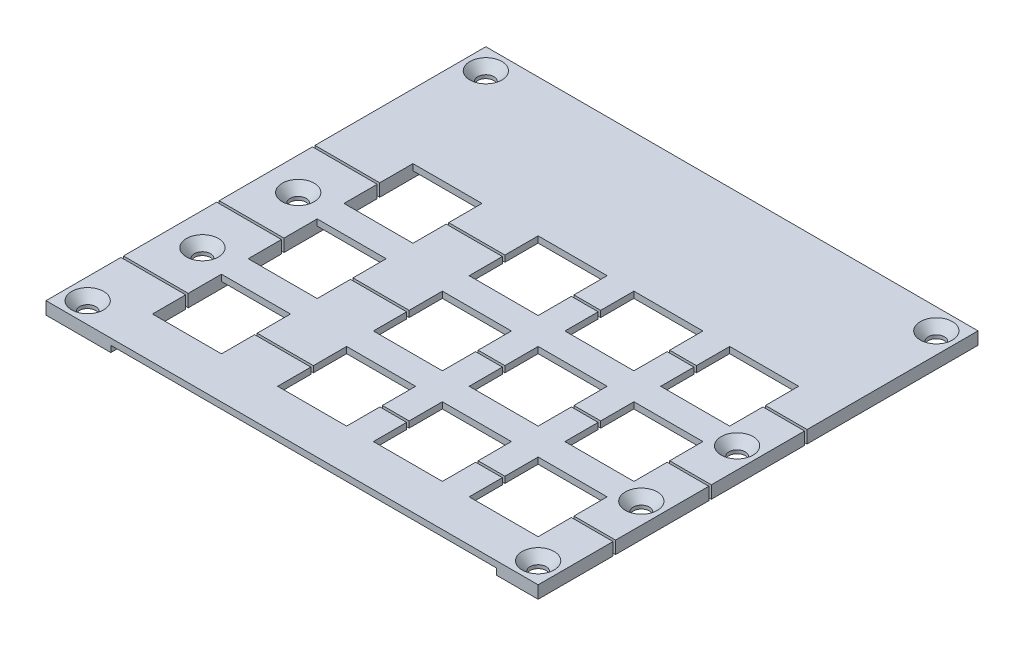
SolidWorks part; units mm, degrees
ref_plane "Front" through (0, 0, 0) normal (0, 0, 1) x (1, 0, 0)
ref_plane "Top" through (0, 0, 0) normal (0, 1, 0) x (1, 0, 0)
ref_plane "Right" through (0, 0, 0) normal (1, 0, 0) x (0, 0, -1)
sketch "Sketch1" plane through (0, 0, 0) normal (0, 1, 0) x (1, 0, 0)
  line L0 (2.6035, 2.6797) -> (8.0137, 2.6797) construction
  line L1 (-49.7332, -44.45) -> (49.7332, -44.45)
  line L2 (-49.7332, -44.45) -> (-49.7332, 44.45)
  line L3 (-49.7332, 44.45) -> (49.7332, 44.45)
  line L4 (49.7332, -44.45) -> (49.7332, 44.45)
  line L5 (-49.7332, -44.45) -> (49.7332, 44.45) construction
  line L6 (-49.7332, 44.45) -> (49.7332, -44.45) construction
  line L7 (-11.3411, 16.6243) -> (2.6035, 16.6243)
  line L8 (-11.3411, 16.6243) -> (-11.3411, 2.6797)
  line L9 (-11.3411, 2.6797) -> (2.6035, 2.6797)
  line L10 (2.6035, 16.6243) -> (2.6035, 2.6797)
  line L11 (8.0137, 16.6243) -> (21.9583, 16.6243)
  line L12 (8.0137, 16.6243) -> (8.0137, 2.6797)
  line L13 (8.0137, 2.6797) -> (21.9583, 2.6797)
  line L14 (21.9583, 16.6243) -> (21.9583, 2.6797)
  line L15 (27.3685, 16.6243) -> (41.3131, 16.6243)
  line L16 (27.3685, 16.6243) -> (27.3685, 2.6797)
  line L17 (27.3685, 2.6797) -> (41.3131, 2.6797)
  line L18 (41.3131, 16.6243) -> (41.3131, 2.6797)
  line L19 (21.9583, 2.6797) -> (27.3685, 2.6797) construction
  line L20 (2.6035, 2.6797) -> (2.6035, -2.7305) construction
  line L21 (-11.3411, -2.7305) -> (2.6035, -2.7305)
  line L22 (-11.3411, -2.7305) -> (-11.3411, -16.6751)
  line L23 (-11.3411, -16.6751) -> (2.6035, -16.6751)
  line L24 (2.6035, -2.7305) -> (2.6035, -16.6751)
  line L25 (8.0137, -2.7305) -> (21.9583, -2.7305)
  line L26 (8.0137, -2.7305) -> (8.0137, -16.6751)
  line L27 (8.0137, -16.6751) -> (21.9583, -16.6751)
  line L28 (21.9583, -2.7305) -> (21.9583, -16.6751)
  line L29 (27.3685, -2.7305) -> (41.3131, -2.7305)
  line L30 (27.3685, -2.7305) -> (27.3685, -16.6751)
  line L31 (27.3685, -16.6751) -> (41.3131, -16.6751)
  line L32 (41.3131, -2.7305) -> (41.3131, -16.6751)
  line L33 (21.9583, 2.6797) -> (21.9583, -2.7305) construction
  line L34 (41.3131, 2.6797) -> (41.3131, -2.7305) construction
  line L35 (2.6035, -22.0853) -> (2.6035, -16.6751) construction
  line L36 (-11.3411, -22.0853) -> (2.6035, -22.0853)
  line L37 (-11.3411, -22.0853) -> (-11.3411, -36.0299)
  line L38 (-11.3411, -36.0299) -> (2.6035, -36.0299)
  line L39 (2.6035, -22.0853) -> (2.6035, -36.0299)
  line L40 (8.0137, -22.0853) -> (21.9583, -22.0853)
  line L41 (8.0137, -22.0853) -> (8.0137, -36.0299)
  line L42 (8.0137, -36.0299) -> (21.9583, -36.0299)
  line L43 (21.9583, -22.0853) -> (21.9583, -36.0299)
  line L44 (27.3685, -22.0853) -> (41.3131, -22.0853)
  line L45 (27.3685, -22.0853) -> (27.3685, -36.0299)
  line L46 (27.3685, -36.0299) -> (41.3131, -36.0299)
  line L47 (41.3131, -22.0853) -> (41.3131, -36.0299)
  line L48 (21.9583, -22.0853) -> (21.9583, -16.6751) construction
  line L49 (41.3131, -16.6751) -> (41.3131, -22.0853) construction
  line L50 (41.3131, -36.0299) -> (49.7332, -36.0299) construction
  line L51 (-13.4112, 0.6096) -> (4.6736, 0.6096) construction
  line L52 (-13.4112, 0.6096) -> (-13.4112, 18.6944) construction
  line L53 (-13.4112, 18.6944) -> (4.6736, 18.6944) construction
  line L54 (4.6736, 0.6096) -> (4.6736, 18.6944) construction
  line L55 (-13.4112, 0.6096) -> (4.6736, 18.6944) construction
  line L56 (-13.4112, 18.6944) -> (4.6736, 0.6096) construction
  line L57 (24.0284, 0.6096) -> (5.9436, 0.6096) construction
  line L58 (24.0284, 0.6096) -> (24.0284, 18.6944) construction
  line L59 (24.0284, 18.6944) -> (5.9436, 18.6944) construction
  line L60 (5.9436, 0.6096) -> (5.9436, 18.6944) construction
  line L61 (24.0284, 0.6096) -> (5.9436, 18.6944) construction
  line L62 (24.0284, 18.6944) -> (5.9436, 0.6096) construction
  line L63 (41.3131, -36.0299) -> (41.3131, -44.45) construction
  line L64 (34.3408, 16.6243) -> (34.3408, 9.652) construction
  line L65 (-36.6395, 2.6797) -> (-22.6949, 2.6797)
  line L66 (-36.6395, 2.6797) -> (-36.6395, 16.6243)
  line L67 (-36.6395, 16.6243) -> (-22.6949, 16.6243)
  line L68 (-22.6949, 2.6797) -> (-22.6949, 16.6243)
  line L69 (-36.6395, 2.6797) -> (-22.6949, 16.6243) construction
  line L70 (-36.6395, 16.6243) -> (-22.6949, 2.6797) construction
  line L71 (-36.6395, -16.6751) -> (-22.6949, -16.6751)
  line L72 (-36.6395, -16.6751) -> (-36.6395, -2.7305)
  line L73 (-36.6395, -2.7305) -> (-22.6949, -2.7305)
  line L74 (-22.6949, -16.6751) -> (-22.6949, -2.7305)
  line L75 (-36.6395, -16.6751) -> (-22.6949, -2.7305) construction
  line L76 (-36.6395, -2.7305) -> (-22.6949, -16.6751) construction
  line L77 (-36.6395, -36.0299) -> (-22.6949, -36.0299)
  line L78 (-36.6395, -36.0299) -> (-36.6395, -22.0853)
  line L79 (-36.6395, -22.0853) -> (-22.6949, -22.0853)
  line L80 (-22.6949, -36.0299) -> (-22.6949, -22.0853)
  line L81 (-36.6395, -36.0299) -> (-22.6949, -22.0853) construction
  line L82 (-36.6395, -22.0853) -> (-22.6949, -36.0299) construction
  line L83 (-43.3832, 18.6563) -> (-15.9512, 18.6563) construction
  line L84 (-43.3832, 18.6563) -> (-43.3832, 0.6477) construction
  line L85 (-43.3832, 0.6477) -> (-15.9512, 0.6477) construction
  line L86 (-15.9512, 18.6563) -> (-15.9512, 0.6477) construction
  line L87 (-43.3832, 18.6563) -> (-15.9512, 0.6477) construction
  line L88 (-43.3832, 0.6477) -> (-15.9512, 18.6563) construction
  line L89 (-43.3832, -0.6985) -> (-15.9512, -0.6985) construction
  line L90 (-43.3832, -0.6985) -> (-43.3832, -18.7071) construction
  line L91 (-43.3832, -18.7071) -> (-15.9512, -18.7071) construction
  line L92 (-15.9512, -0.6985) -> (-15.9512, -18.7071) construction
  line L93 (-43.3832, -0.6985) -> (-15.9512, -18.7071) construction
  line L94 (-43.3832, -18.7071) -> (-15.9512, -0.6985) construction
  line L95 (-43.3832, -20.0533) -> (-15.9512, -20.0533)
  line L96 (-43.3832, -20.0533) -> (-43.3832, -38.0619) construction
  line L97 (-43.3832, -38.0619) -> (-15.9512, -38.0619) construction
  line L98 (-15.9512, -20.0533) -> (-15.9512, -38.0619) construction
  line L99 (-43.3832, -20.0533) -> (-15.9512, -38.0619) construction
  line L100 (-43.3832, -38.0619) -> (-15.9512, -20.0533) construction
  line L101 (25.2984, 0.6096) -> (43.3832, 0.6096) construction
  line L102 (25.2984, 0.6096) -> (25.2984, 18.6944) construction
  line L103 (25.2984, 18.6944) -> (43.3832, 18.6944) construction
  line L104 (43.3832, 0.6096) -> (43.3832, 18.6944) construction
  line L105 (25.2984, 0.6096) -> (43.3832, 18.6944) construction
  line L106 (25.2984, 18.6944) -> (43.3832, 0.6096) construction
  point P0 (0, 0)
  point P42 (14.986, 9.652)
  point P43 (-4.3688, 9.652)
  point P49 (-4.3688, 16.6243)
  point P51 (-11.3411, 9.652)
  point P54 (-29.6672, 9.652)
  point P55 (14.986, 16.6243)
  point P57 (8.0137, 9.652)
  point P63 (-29.6672, -9.7028)
  point P68 (-29.6672, -29.0576)
  point P73 (-29.6672, -9.7028)
  point P75 (-29.6672, 9.652)
  point P83 (-29.6672, -29.0576)
  point P89 (34.3408, 9.652)
  dimension "D1" = 88.9
  dimension "D2" = 6.35
  dimension "D3" = 13.9446
  dimension "D4" = 18.0848
  dimension "D5" = 1.27
  dimension "D6" = 6.35
  dimension "D7" = 18.0086
  dimension "D8" = 27.432
  dimension "D9" = 2.54
extrude "Boss-Extrude1" add sketch "Sketch1" along normal blind 1.27
sketch "Sketch2" plane through (0, 1.27, 0) normal (0, 1, 0) x (1, 0, 0)
  line L0 (-49.7332, 9.652) -> (49.7332, 9.652)
  line L1 (-49.7332, -44.45) -> (-49.7332, 44.45) construction
  line L2 (49.7332, -44.45) -> (49.7332, 44.45) construction
  line L3 (27.3685, 16.6243) -> (27.3685, 2.6797) construction
  line L4 (-49.7332, -9.7028) -> (49.7332, -9.7028)
  line L5 (41.3131, -2.7305) -> (41.3131, -16.6751) construction
  line L6 (41.3131, -22.0853) -> (41.3131, -36.0299) construction
  line L7 (-49.7332, -29.0576) -> (49.7332, -29.0576)
  point P8 (27.3685, 9.652)
  point P15 (41.3131, -9.7028)
  point P18 (41.3131, -29.0576)
sketch "Sketch4" plane through (0, 1.27, 0) normal (0, 1, 0) x (1, 0, 0)
  line L0 (-49.7332, 9.652) -> (49.7332, 9.652) construction
  line L1 (-49.7332, -9.7028) -> (49.7332, -9.7028) construction
  line L2 (-49.7332, -29.0576) -> (49.7332, -29.0576) construction
  line L3 (2.6035, 16.6243) -> (8.0137, 16.6243) construction
  line L4 (21.9583, 16.6243) -> (27.3685, 16.6243) construction
  line L5 (-22.6949, 16.6243) -> (-11.3411, 16.6243) construction
  line L6 (41.3131, 16.6243) -> (49.7332, 16.6243) construction
  line L7 (49.7332, -44.45) -> (49.7332, 44.45) construction
  line L8 (-36.6395, 16.6243) -> (-49.7332, 16.6243) construction
  line L9 (-49.7332, -44.45) -> (-49.7332, 44.45) construction
  point P0 (-17.018, 9.652)
  point P1 (-17.018, -9.7028)
  point P4 (-17.018, -29.0576)
  point P7 (5.3086, -29.0576)
  point P10 (5.3086, -9.7028)
  point P11 (5.3086, 9.652)
  point P12 (24.6634, 9.652)
  point P13 (24.6634, -9.7028)
  point P14 (24.6634, -29.0576)
  point P15 (45.5232, 9.652)
  point P16 (45.5232, -9.7028)
  point P17 (45.5232, -29.0576)
  point P18 (-43.1864, 9.652)
  point P19 (-43.1864, -9.7028)
  point P20 (-43.1864, -29.0576)
  point P43 (5.3086, 16.6243)
  point P44 (24.6634, 16.6243)
  point P45 (-43.1864, 16.6243)
  point P46 (-17.018, 16.6243)
  point P47 (45.5232, 16.6243)
sketch "Sketch6" plane through (0, 0, 0) normal (0, -1, 0) x (1, 0, 0)
  line L0 (-49.7332, -44.45) -> (49.7332, -44.45) construction
  line L1 (-49.7332, 44.45) -> (-36.6395, 44.45)
  line L2 (-49.7332, 44.45) -> (-49.7332, -44.45)
  line L3 (-49.7332, -44.45) -> (-36.6395, -44.45)
  line L4 (-36.6395, 44.45) -> (-36.6395, -44.45)
  line L5 (-49.7332, 44.45) -> (49.7332, 44.45) construction
  line L6 (41.3131, 44.45) -> (49.7332, 44.45)
  line L7 (41.3131, 44.45) -> (41.3131, -44.45)
  line L8 (41.3131, -44.45) -> (49.7332, -44.45)
  line L9 (49.7332, 44.45) -> (49.7332, -44.45)
  line L10 (41.3131, 22.0853) -> (41.3131, 36.0299) construction
  line L11 (-36.6395, 36.0299) -> (-36.6395, 22.0853) construction
extrude "Boss-Extrude2" add sketch "Sketch6" along normal blind 1.27
extrude "Cut-Extrude-Thin2" cut sketch "Sketch2" against normal through all thin thin type mid plane wall 0.508
sketch "Sketch8" plane through (0, 1.27, 0) normal (0, 1, 0) x (1, 0, 0)
  line L0 (41.3131, -36.0299) -> (41.3131, -44.45) construction
  line L1 (-49.7332, 9.906) -> (-36.6395, 9.906) construction
  line L2 (41.3131, 9.906) -> (49.7332, 9.906) construction
  line L3 (49.7332, -28.8036) -> (49.7332, -9.9568) construction
  line L4 (49.7332, -9.4488) -> (49.7332, 9.398) construction
  line L5 (0, 0) -> (0, -9.9001) construction
  line L6 (-49.7332, -44.45) -> (49.7332, -44.45) construction
  line L7 (-9.6807, 0) -> (8.7732, 0) construction
  point P0 (-45.5232, 40.24)
  point P1 (-43.1864, -0.0254)
  point P2 (-43.1864, -19.3802)
  point P3 (-45.5232, -40.24)
  point P4 (45.5232, -40.24)
  point P5 (45.5232, -19.3802)
  point P6 (45.5232, -0.0254)
  point P7 (45.5232, 40.24)
  point P10 (-43.1864, 9.906)
  point P13 (45.5232, 9.906)
  point P16 (49.7332, -19.3802)
  point P19 (49.7332, -0.0254)
  point P22 (41.3131, -40.24)
  point P31 (0, 0)
hole_wizard "CSK for #4 Flat Head Socket Cap Screw1" positions "3DSketch2" profile "Sketch7" countersink size "#4" standard "ANSI Inch" end condition up to next
sketch3d "3DSketch2"
  point P19 (-45.5232, 1.27, -40.24)
  point P22 (45.5232, 1.27, -40.24)
  point P25 (45.5232, 1.27, 40.24)
  point P28 (-45.5232, 1.27, 40.24)
  point P31 (-43.1864, 1.27, 0.0254)
  point P34 (-43.1864, 1.27, 19.3802)
  point P37 (45.5232, 1.27, 19.3802)
  point P40 (45.5232, 1.27, 0.0254)
sketch "Sketch7" plane through (-45.5232, 1.27, -40.24) normal (1, 0, 0) x (0, 0, 1)
  line L0 (0, 0) -> (0, 2.54)
  line L1 (0, 2.54) -> (1.6319, 2.54)
  line L2 (1.6319, 2.54) -> (1.6319, 1.8481)
  line L3 (1.6319, 1.8481) -> (3.2385, 0)
  line L5 (3.2385, 0) -> (0, 0)
  line L6 (-1.632, 1.8481) -> (-3.2385, 0) construction
  line L11 (0, -6.35) -> (0, 107.95) construction
  dimension "Thru Hole Dia." = 3.2639
  dimension "Thru Hole Depth" = 2.54
  dimension "Near C'Sink Dia." = 6.477
  dimension "Near C'Sink Angle" = 82
